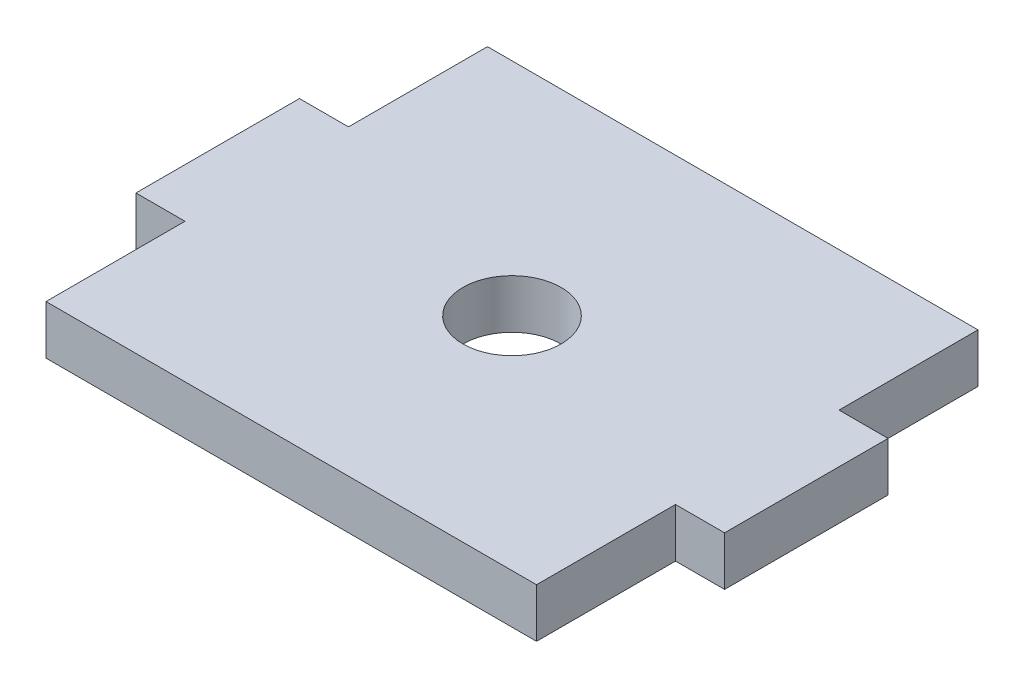
SolidWorks part; units mm, degrees
ref_plane "Alzado" through (0, 0, 0) normal (0, 0, 1) x (1, 0, 0)
ref_plane "Planta" through (0, 0, 0) normal (0, 1, 0) x (1, 0, 0)
ref_plane "Vista lateral" through (0, 0, 0) normal (1, 0, 0) x (0, 0, -1)
sketch "Croquis1" plane through (0, 0, 0) normal (0, 1, 0) x (1, 0, 0)
  line L0 (0, 0) -> (30, 0)
  line L1 (0, 0) -> (0, 8.5)
  line L2 (0, 27) -> (30, 27)
  line L3 (30, 27) -> (30, 18.5)
  line L5 (-3, 13.5) -> (-3, 18.5)
  line L6 (-3, 18.5) -> (0, 18.5)
  line L7 (-3, 13.5) -> (-3, 8.5)
  line L8 (-3, 8.5) -> (0, 8.5)
  line L10 (33, 8.5) -> (30, 8.5)
  line L11 (33, 13.5) -> (33, 8.5)
  line L12 (33, 18.5) -> (30, 18.5)
  line L13 (33, 13.5) -> (33, 18.5)
  line L14 (30, 8.5) -> (30, 0)
  line L15 (0, 18.5) -> (0, 27)
  circle A0 centre (15, 13.5) radius 3
  dimension "D3" = 6
  dimension "D1" = 30
  dimension "D2" = 27
  dimension "D4" = 5
  dimension "D5" = 5
extrude "Saliente-Extruir1" add sketch "Croquis1" along normal blind 3
